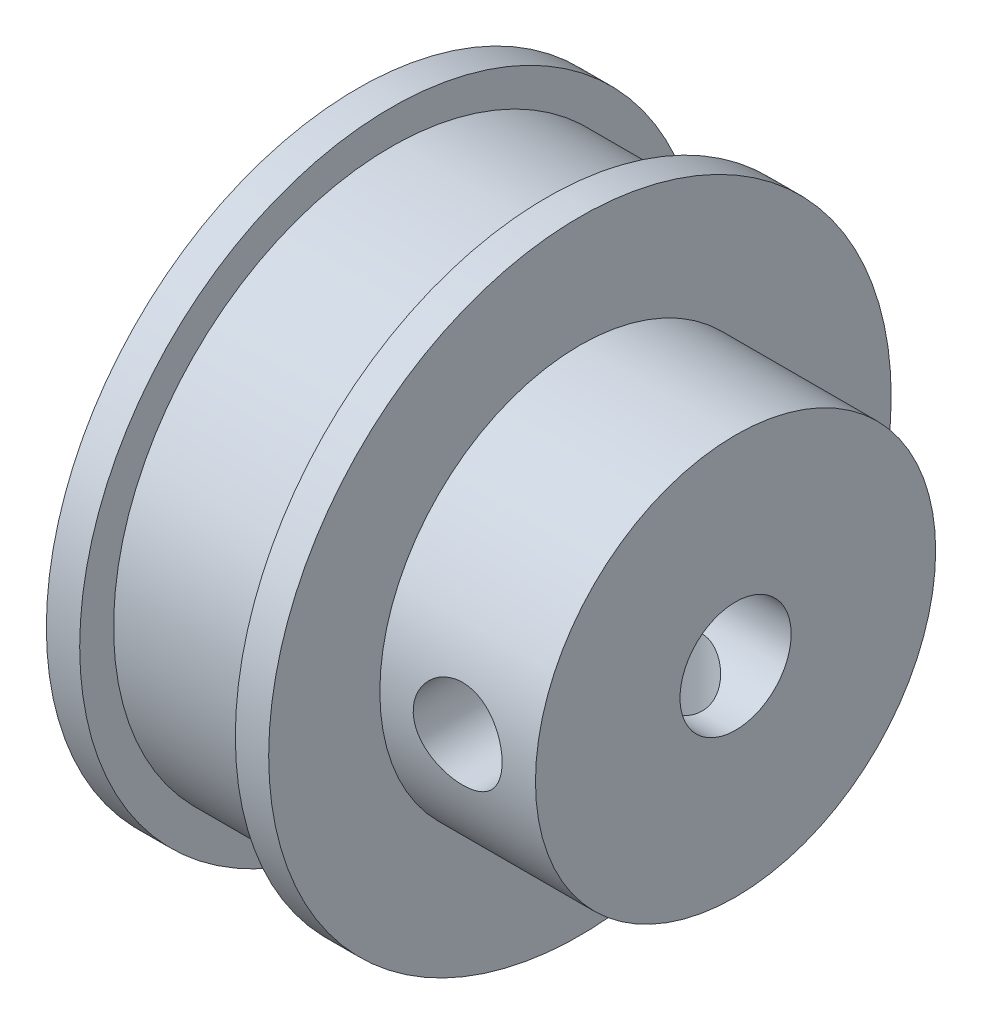
SolidWorks part; units mm, degrees
ref_plane "Front Plane" through (0, 0, 0) normal (0, 0, 1) x (1, 0, 0)
ref_plane "Top Plane" through (0, 0, 0) normal (0, 1, 0) x (1, 0, 0)
ref_plane "Right Plane" through (0, 0, 0) normal (1, 0, 0) x (0, 0, -1)
sketch "Sketch1" plane through (0, 0, 0) normal (0, 0, 1) x (1, 0, 0)
  line L0 (0, 2.5) -> (17, 2.5)
  line L1 (17, 2.5) -> (17, 9)
  line L2 (17, 9) -> (10, 9)
  line L3 (10, 9) -> (10, 14)
  line L4 (10, 14) -> (8.5, 14)
  line L5 (8.5, 14) -> (8.5, 12.475)
  line L6 (8.5, 12.475) -> (1.5, 12.475)
  line L7 (1.5, 12.475) -> (1.5, 14)
  line L8 (1.5, 14) -> (0, 14)
  line L9 (0, 14) -> (0, 2.5)
  point P8 (9.25, 14)
  dimension "D1" = 9
  dimension "D2" = 2.5
  dimension "D3" = 14
  dimension "D4" = 12.475
  dimension "D5" = 7
  dimension "D6" = 17
  dimension "D7" = 7
  dimension "D8" = 1.5
ref_axis "Axis1" through (17.85, 0, 0) along (-1, 0, 0)
revolve "Revolve1" add sketch "Sketch1" angle 360 about axis through (17.85, 0, 0) along (-1, 0, 0)
sketch "Sketch2" plane through (0, 0, 0) normal (0, 1, 0) x (1, 0, 0)
  line L0 (17.85, 0) -> (-0.85, 0) construction
  line L1 (17, -9) -> (17, 9) construction
  circle A0 centre (13.5, 0) radius 2
  dimension "D1" = 4
  dimension "D2" = 3.5
extrude "Cut-Extrude1" cut sketch "Sketch2" against normal up to next
pattern_circular "CirPattern1" count 2 over 90 about axis through (17.85, 0, 0) along (-1, 0, 0) of "Cut-Extrude1"
